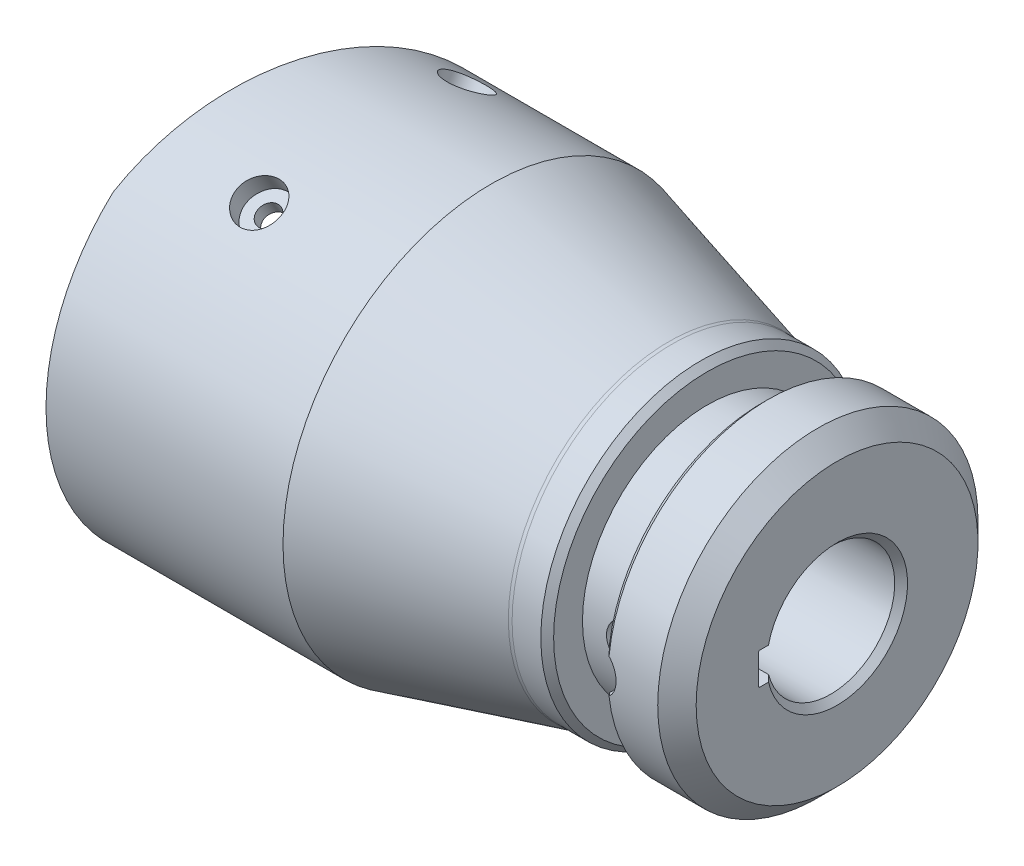
SolidWorks part; units mm, degrees
material "2014-T6"
ref_plane "Спереди" through (0, 0, 0) normal (0, 0, 1) x (1, 0, 0)
ref_plane "Сверху" through (0, 0, 0) normal (0, 1, 0) x (1, 0, 0)
ref_plane "Справа" through (0, 0, 0) normal (1, 0, 0) x (0, 0, -1)
other "Configuration Table"
sketch "Эскиз1" plane through (0, 0, 0) normal (0, 0, 1) x (1, 0, 0)
  line L0 (0, 32.5) -> (37, 32.5)
  line L1 (37, 32.5) -> (64.7457, 25.0681)
  line L2 (65.2632, 25) -> (69.75, 25)
  line L3 (69.75, 25) -> (70.75, 24)
  line L4 (70.75, 24) -> (70.75, 19.5)
  line L5 (70.75, 19.5) -> (79.25, 19.5)
  line L6 (79.25, 19.5) -> (79.25, 24)
  line L7 (79.25, 24) -> (80.25, 25)
  line L8 (80.25, 25) -> (88, 25)
  line L9 (88, 25) -> (91, 22)
  line L10 (91, 22) -> (91, 11)
  line L11 (91, 11) -> (90, 10)
  line L12 (90, 10) -> (61, 10)
  line L13 (61, 10) -> (61, 19)
  line L14 (60, 20) -> (25, 20)
  line L15 (25, 20) -> (25, 27.1)
  line L16 (24.6, 27.5) -> (0, 27.5)
  line L17 (0, 27.5) -> (0, 32.5)
  line L18 (0, 0) -> (100, 0) construction
  arc A0 (64.7457, 25.0681) -> (65.2632, 25) centre (65.2632, 27) ccw
  arc A1 (61, 19) -> (60, 20) centre (60, 19) ccw
  arc A2 (25, 27.1) -> (24.6, 27.5) centre (24.6, 27.1) ccw
revolve "Точеный профиль" add sketch "Эскиз1" angle 360 about L18
sketch "Эскиз2" plane through (0, 0, 0) normal (0, 1, 0) x (1, 0, 0)
  line L0 (-25, 50) -> (15.3041, 50)
  line L1 (15.3041, 50) -> (-5.9516, -50)
  line L2 (-5.9516, -50) -> (-25, -50)
  line L3 (-25, -50) -> (-25, 50)
extrude "Наклон торца 12 градусов" cut sketch "Эскиз2" against normal through all and the other way through all
sketch "Эскиз3" plane through (0, 0, 0) normal (1, 0, 0) x (0, 0, -1)
  line L0 (0, -2.5) -> (0, 2.5)
  line L1 (0, 2.5) -> (-12.05, 2.5)
  line L2 (-12.3, 2.25) -> (-12.3, -2.25)
  line L3 (-12.05, -2.5) -> (0, -2.5)
  arc A0 (-12.05, 2.5) -> (-12.3, 2.25) centre (-12.05, 2.25) ccw
  arc A1 (-12.3, -2.25) -> (-12.05, -2.5) centre (-12.05, -2.25) ccw
extrude "Паз 5 R0.25" cut sketch "Эскиз3" along normal blind 31 from offset 61
ref_plane "Плоскость отверстий 30" through (0, 0, 0) normal (0, -0.5, 0.866) x (1, 0, 0)
sketch "Эскиз4" plane through (0, 0, 0) normal (0, -0.5, 0.866) x (1, 0, 0)
  line L0 (17, -26) -> (18.7, -26)
  line L1 (18.7, -26) -> (18.7, -29.5)
  line L2 (18.7, -29.5) -> (20.5, -29.5)
  line L3 (20.5, -29.5) -> (20.5, -40)
  line L4 (20.5, -40) -> (17, -40)
  line L5 (17, -40) -> (17, -26)
  line L6 (17, -20) -> (17, -45) construction
revolve "Радиальное отверстие M4 30 -1" cut sketch "Эскиз4" angle 360 about L6
cosmetic thread "Условное изображение резьбы2" parameters "D2"=4
sketch "Эскиз5" plane through (0, 0, 0) normal (0, -0.5, 0.866) x (1, 0, 0)
  line L0 (17, 26) -> (18.7, 26)
  line L1 (18.7, 26) -> (18.7, 29.5)
  line L2 (18.7, 29.5) -> (20.5, 29.5)
  line L3 (20.5, 29.5) -> (20.5, 40)
  line L4 (20.5, 40) -> (17, 40)
  line L5 (17, 40) -> (17, 26)
  line L6 (17, 20) -> (17, 45) construction
revolve "Радиальное отверстие M4 30 1" cut sketch "Эскиз5" angle 360 about L6
cosmetic thread "Условное изображение резьбы3" parameters "D2"=4
ref_plane "Плоскость отверстий 150" through (0, 0, 0) normal (0, -0.5, -0.866) x (1, 0, 0)
sketch "Эскиз6" plane through (0, 0, 0) normal (0, -0.5, -0.866) x (1, 0, 0)
  line L0 (17, -26) -> (18.7, -26)
  line L1 (18.7, -26) -> (18.7, -29.5)
  line L2 (18.7, -29.5) -> (20.5, -29.5)
  line L3 (20.5, -29.5) -> (20.5, -40)
  line L4 (20.5, -40) -> (17, -40)
  line L5 (17, -40) -> (17, -26)
  line L6 (17, -20) -> (17, -45) construction
revolve "Радиальное отверстие M4 150 -1" cut sketch "Эскиз6" angle 360 about L6
cosmetic thread "Условное изображение резьбы4" parameters "D2"=4
sketch "Эскиз7" plane through (0, 0, 0) normal (0, -0.5, -0.866) x (1, 0, 0)
  line L0 (17, 26) -> (18.7, 26)
  line L1 (18.7, 26) -> (18.7, 29.5)
  line L2 (18.7, 29.5) -> (20.5, 29.5)
  line L3 (20.5, 29.5) -> (20.5, 40)
  line L4 (20.5, 40) -> (17, 40)
  line L5 (17, 40) -> (17, 26)
  line L6 (17, 20) -> (17, 45) construction
revolve "Радиальное отверстие M4 150 1" cut sketch "Эскиз7" angle 360 about L6
cosmetic thread "Условное изображение резьбы5" parameters "D2"=4
sketch "Эскиз8" plane through (0, 0, 0) normal (0, 1, 0) x (1, 0, 0)
  line L0 (78, -8) -> (79.8, -8)
  line L1 (79.8, -8) -> (79.8, -15)
  line L2 (79.8, -15) -> (81.5, -15)
  line L3 (81.5, -15) -> (81.5, -35)
  line L4 (81.5, -35) -> (78, -35)
  line L5 (78, -35) -> (78, -8)
  line L6 (78, 0) -> (78, -40) construction
revolve "Радиальное отверстие 3.6 цековка 7" cut sketch "Эскиз8" angle 360 about L6
cosmetic thread "Условное изображение резьбы6" parameters "D1"=2.7, "D2"=4.6
